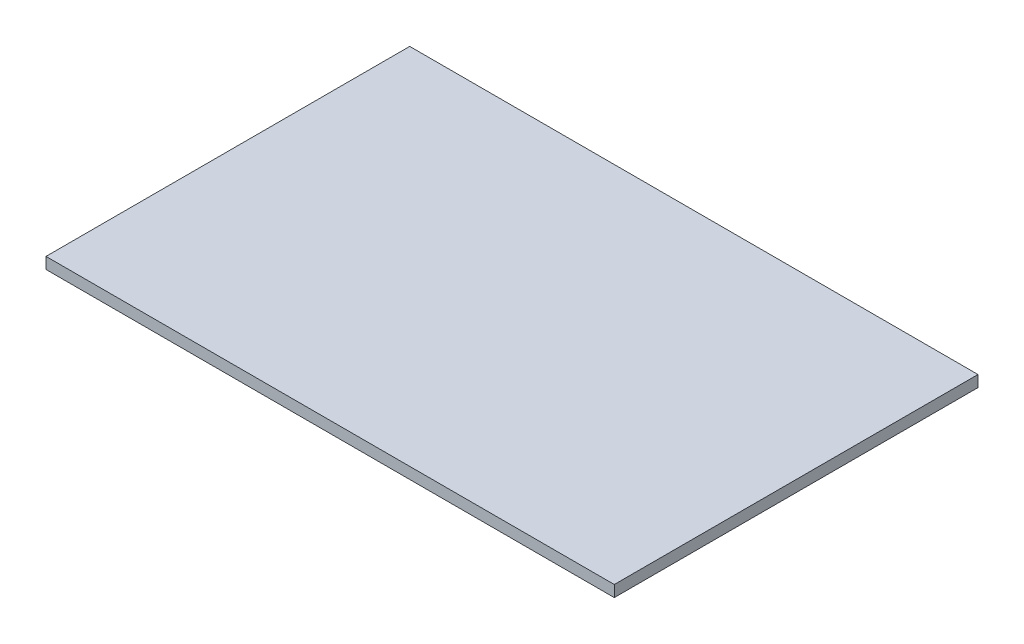
SolidWorks part; units mm, degrees
ref_plane "前视基准面" through (0, 0, 0) normal (0, 0, 1) x (1, 0, 0)
ref_plane "上视基准面" through (0, 0, 0) normal (0, 1, 0) x (1, 0, 0)
ref_plane "右视基准面" through (0, 0, 0) normal (1, 0, 0) x (0, 0, -1)
sketch "草图2" plane through (0, 0, 0) normal (0, 1, 0) x (1, 0, 0)
  line L1 (-125, -80) -> (125, -80)
  line L2 (-125, -80) -> (-125, 80)
  line L3 (-125, 80) -> (125, 80)
  line L4 (125, -80) -> (125, 80)
  line L5 (-125, -80) -> (125, 80) construction
  line L6 (-125, 80) -> (125, -80) construction
  point P0 (0, 0)
  dimension "D1" = 250
  dimension "D2" = 160
extrude "凸台-拉伸1" add sketch "草图2" along normal blind 5
